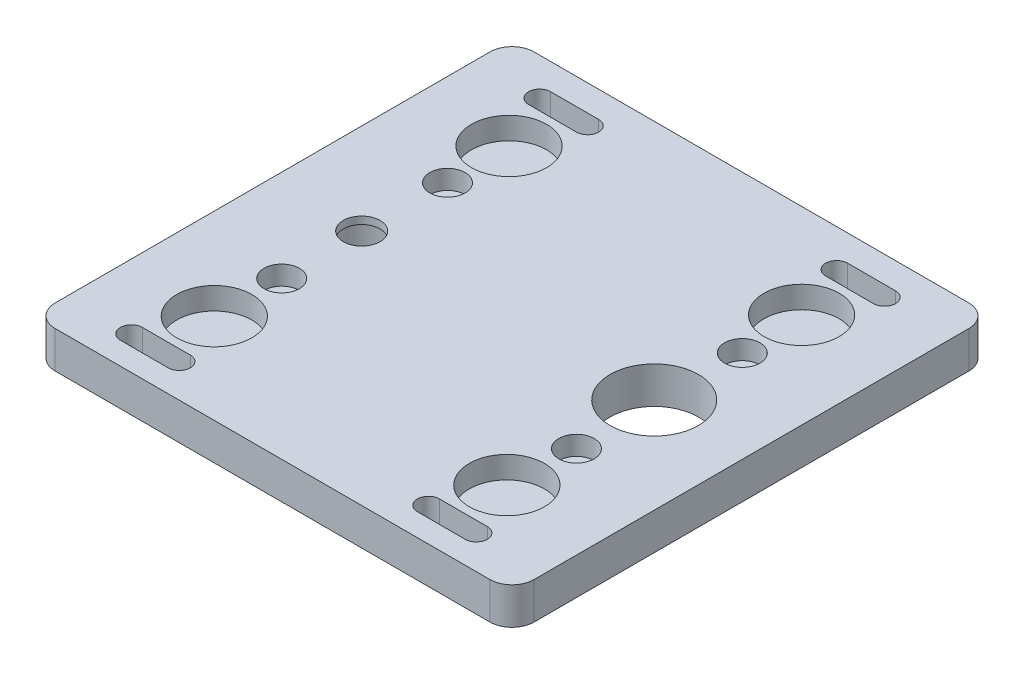
SolidWorks part; units mm, degrees
ref_plane "Alzado" through (0, 0, 0) normal (0, 0, 1) x (1, 0, 0)
ref_plane "Planta" through (0, 0, 0) normal (0, 1, 0) x (1, 0, 0)
ref_plane "Vista lateral" through (0, 0, 0) normal (1, 0, 0) x (0, 0, -1)
sketch "Croquis1" plane through (0, 0, 0) normal (0, -1, 0) x (1, 0, 0)
  line L1 (-47.7412, -0.2707) -> (17.2588, -0.2707)
  line L2 (-47.7412, -0.2707) -> (-47.7412, -65.2707)
  line L3 (-47.7412, -65.2707) -> (17.2588, -65.2707)
  line L4 (17.2588, -0.2707) -> (17.2588, -65.2707)
  line L5 (-32.4392, -6.3207) -> (-38.9392, -6.3207) construction
  line L6 (-38.9392, -3.3207) -> (-32.4392, -3.3207) construction
  line L7 (-32.4392, -6.3207) -> (-38.9392, -6.3207)
  line L8 (-38.9392, -3.3207) -> (-32.4392, -3.3207)
  line L9 (1.3608, -3.3207) -> (7.8608, -3.3207) construction
  line L10 (7.8608, -6.3207) -> (1.3608, -6.3207) construction
  line L11 (7.8608, -6.3207) -> (1.3608, -6.3207)
  line L12 (1.3608, -3.3207) -> (7.8608, -3.3207)
  line L13 (-38.9392, -58.7207) -> (-32.4392, -58.7207) construction
  line L14 (-32.4392, -61.7207) -> (-38.9392, -61.7207) construction
  line L15 (-38.9392, -58.7207) -> (-32.4392, -58.7207)
  line L16 (-32.4392, -61.7207) -> (-38.9392, -61.7207)
  line L17 (7.8608, -61.7207) -> (1.3608, -61.7207) construction
  line L18 (1.3608, -58.7207) -> (7.8608, -58.7207) construction
  line L19 (7.8608, -61.7207) -> (1.3608, -61.7207)
  line L20 (1.3608, -58.7207) -> (7.8608, -58.7207)
  circle A1 centre (-35.3892, -12.5207) radius 5.1
  circle A2 centre (4.3108, -12.5207) radius 5.1
  circle A3 centre (-35.3892, -52.5207) radius 5.1
  circle A4 centre (4.3108, -52.5207) radius 5.1
  circle A5 centre (4.3108, -32.5207) radius 6
  arc A11 (-38.9392, -3.3207) -> (-38.9392, -6.3207) centre (-38.9392, -4.8207) ccw construction
  arc A12 (-32.4392, -6.3207) -> (-32.4392, -3.3207) centre (-32.4392, -4.8207) ccw construction
  arc A13 (-38.9392, -3.3207) -> (-38.9392, -6.3207) centre (-38.9392, -4.8207) ccw
  arc A14 (-32.4392, -6.3207) -> (-32.4392, -3.3207) centre (-32.4392, -4.8207) ccw
  arc A15 (1.3608, -3.3207) -> (1.3608, -6.3207) centre (1.3608, -4.8207) ccw construction
  arc A16 (7.8608, -6.3207) -> (7.8608, -3.3207) centre (7.8608, -4.8207) ccw construction
  arc A17 (7.8608, -6.3207) -> (7.8608, -3.3207) centre (7.8608, -4.8207) ccw
  arc A18 (1.3608, -3.3207) -> (1.3608, -6.3207) centre (1.3608, -4.8207) ccw
  arc A19 (-32.4392, -61.7207) -> (-32.4392, -58.7207) centre (-32.4392, -60.2207) ccw construction
  arc A20 (-38.9392, -58.7207) -> (-38.9392, -61.7207) centre (-38.9392, -60.2207) ccw construction
  arc A21 (-32.4392, -61.7207) -> (-32.4392, -58.7207) centre (-32.4392, -60.2207) ccw
  arc A22 (-38.9392, -58.7207) -> (-38.9392, -61.7207) centre (-38.9392, -60.2207) ccw
  arc A23 (7.8608, -61.7207) -> (7.8608, -58.7207) centre (7.8608, -60.2207) ccw construction
  arc A24 (1.3608, -58.7207) -> (1.3608, -61.7207) centre (1.3608, -60.2207) ccw construction
  arc A25 (7.8608, -61.7207) -> (7.8608, -58.7207) centre (7.8608, -60.2207) ccw
  arc A26 (1.3608, -58.7207) -> (1.3608, -61.7207) centre (1.3608, -60.2207) ccw
  circle A27 centre (-35.3892, -32.5207) radius 4.6
  dimension "D1" = 10.2
  dimension "D4" = 12
  dimension "D5" = 9.2
  dimension "D2" = 65
  dimension "D3" = 65
extrude "Saliente-Extruir1" add sketch "Croquis1" along normal blind 5
fillet "Redondeo2" radius 3 4 edges at (17.2588, -2.5, -0.2707) (-47.7412, -2.5, -65.2707) (17.2588, -2.5, -65.2707) (-47.7412, -2.5, -0.2707)
sketch "Croquis2" plane through (0, 0, 0) normal (0, 1, 0) x (1, 0, 0)
  circle A0 centre (-35.3892, 32.5207) radius 4.6
extrude "Saliente-Extruir2" add sketch "Croquis2" against normal blind 1
sketch "Croquis3" plane through (0, -1, 0) normal (0, -1, 0) x (1, 0, 0)
  circle A0 centre (-35.3892, -32.5207) radius 2.5
  dimension "D1" = 5
extrude "Cortar-Extruir1" cut sketch "Croquis3" against normal blind 1
sketch "Croquis4" plane through (0, -5, 0) normal (0, -1, 0) x (1, 0, 0)
  circle A0 centre (-35.2412, -44.0207) radius 2.4
  circle A1 centre (-35.2412, -21.5207) radius 2.4
  circle A2 centre (4.7588, -21.5207) radius 2.4
  circle A3 centre (4.7588, -44.0207) radius 2.4
  dimension "D1" = 4.8
extrude "Cortar-Extruir2" cut sketch "Croquis4" against normal blind 10
sketch "Croquis5" plane through (0, -5, 0) normal (0, -1, 0) x (1, 0, 0)
  circle A0 centre (-35.2412, -44.0207) radius 2.4
  circle A1 centre (-35.2412, -44.0207) radius 1.25
  circle A2 centre (-35.2412, -44.0207) radius 2.4 construction
  circle A3 centre (-35.2412, -21.5207) radius 1.25
  circle A4 centre (-35.2412, -21.5207) radius 2.4
  circle A5 centre (4.7588, -21.5207) radius 1.25
  circle A6 centre (4.7588, -21.5207) radius 2.4
  circle A7 centre (4.7588, -44.0207) radius 2.4
  circle A8 centre (4.7588, -44.0207) radius 1.25
  dimension "D1" = 2.5
extrude "Saliente-Extruir3" add sketch "Croquis5" against normal blind 2.4
sketch "Croquis6" plane through (0, -5, 0) normal (0, -1, 0) x (1, 0, 0)
  circle A0 centre (-35.3892, -52.5207) radius 5.1
  circle A1 centre (4.3108, -52.5207) radius 5.1
  circle A2 centre (4.3108, -12.5207) radius 5.1
  circle A3 centre (-35.3892, -12.5207) radius 5.1
extrude "Saliente-Extruir4" add sketch "Croquis6" against normal blind 2
